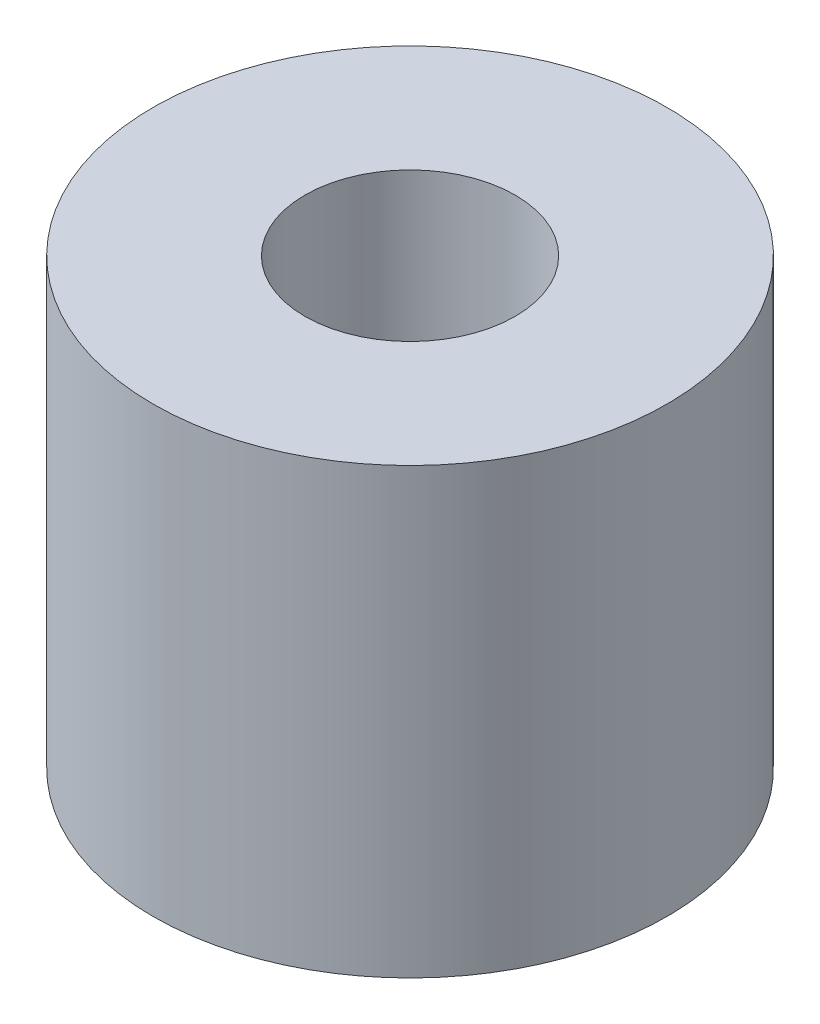
SolidWorks part; units mm, degrees
material "Polyurethane Foam Flexible"
ref_plane "Front" through (0, 0, 0) normal (0, 0, 1) x (1, 0, 0)
ref_plane "Top" through (0, 0, 0) normal (0, 1, 0) x (1, 0, 0)
ref_plane "Right" through (0, 0, 0) normal (1, 0, 0) x (0, 0, -1)
sketch "Sketch1" plane through (0, 0, 0) normal (0, 1, 0) x (1, 0, 0)
  circle A0 centre (0, 0) radius 11
  circle A1 centre (0, 0) radius 4.5
extrude "Boss-Extrude1" add sketch "Sketch1" along normal blind 19
